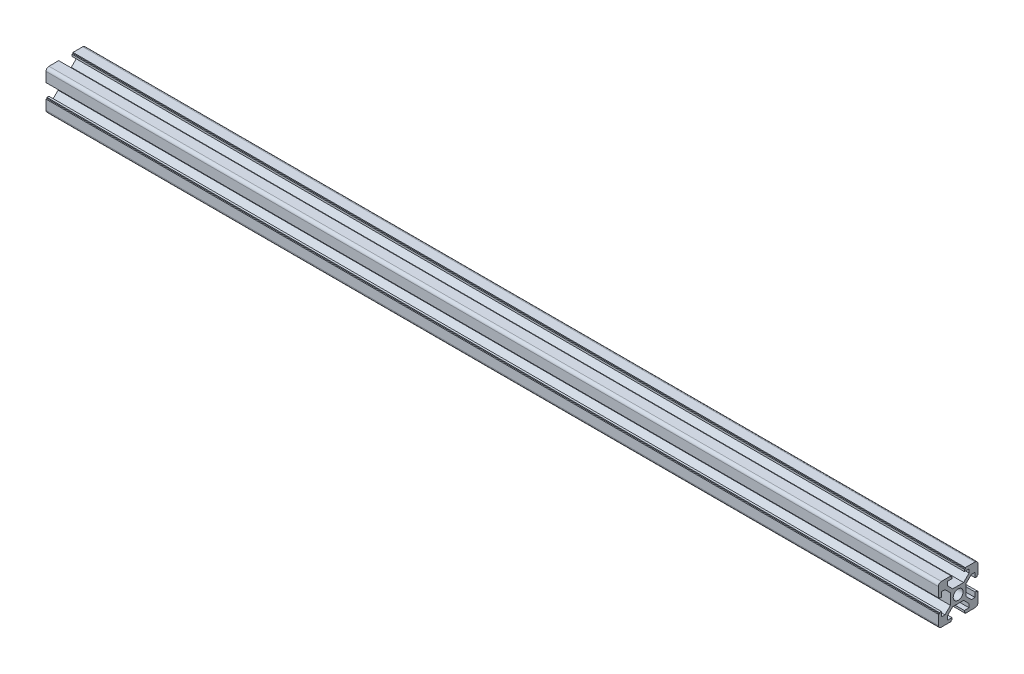
SolidWorks part; units mm, degrees
ref_plane "前视基准面" through (0, 0, 0) normal (0, 0, 1) x (1, 0, 0)
ref_plane "上视基准面" through (0, 0, 0) normal (0, 1, 0) x (1, 0, 0)
ref_plane "右视基准面" through (0, 0, 0) normal (1, 0, 0) x (0, 0, -1)
other "Configuration Table"
sketch "草图1" plane through (0, 0, 0) normal (0, 1, 0) x (1, 0, 0)
  line L0 (0, 0) -> (450, 0)
  dimension "D1" = 450
other "铝型材 20 X 20 X R1.5(1)"
ref_plane "基准面1" through (0, 0, 0) normal (1, 0, 0) x (0, 0, -1)
sketch "Sketch1" plane through (0, 0, 0) normal (1, 0, 0) x (0, 0, -1)
  line L0 (-3.6, 10) -> (-3.6, 9.5)
  line L1 (-3.6, 9.5) -> (-3.1, 9.5)
  line L2 (-3.1, 9.5) -> (-3.1, 8.5)
  line L3 (-3.1, 8.5) -> (-5.5, 8.5)
  line L4 (-8.5, -10) -> (-3.6, -10)
  line L5 (-10, -8.5) -> (-10, -3.6)
  line L6 (8.5, 10) -> (3.6, 10)
  line L7 (10, 8.5) -> (10, 3.6)
  line L8 (0, 14.8756) -> (0, 0) construction
  line L9 (0, 0) -> (14.1675, 0) construction
  line L10 (-5.5, 8.5) -> (-5.5, 6.65)
  line L11 (-5.5, 6.65) -> (-2.75, 3.9)
  line L12 (-2.75, 3.9) -> (2.75, 3.9)
  line L13 (5.5, 6.65) -> (2.75, 3.9)
  line L14 (5.5, 8.5) -> (5.5, 6.65)
  line L15 (3.1, 8.5) -> (5.5, 8.5)
  line L16 (3.1, 9.5) -> (3.1, 8.5)
  line L17 (3.6, 9.5) -> (3.1, 9.5)
  line L18 (3.6, 10) -> (3.6, 9.5)
  line L19 (-3.6, 10) -> (-8.5, 10)
  line L20 (10, 3.6) -> (9.5, 3.6)
  line L21 (9.5, 3.6) -> (9.5, 3.1)
  line L22 (9.5, 3.1) -> (8.5, 3.1)
  line L23 (8.5, 3.1) -> (8.5, 5.5)
  line L24 (8.5, 5.5) -> (6.65, 5.5)
  line L25 (6.65, 5.5) -> (3.9, 2.75)
  line L26 (3.9, 2.75) -> (3.9, -2.75)
  line L27 (6.65, -5.5) -> (3.9, -2.75)
  line L28 (8.5, -5.5) -> (6.65, -5.5)
  line L29 (8.5, -3.1) -> (8.5, -5.5)
  line L30 (9.5, -3.1) -> (8.5, -3.1)
  line L31 (9.5, -3.6) -> (9.5, -3.1)
  line L32 (10, -3.6) -> (9.5, -3.6)
  line L33 (3.6, -10) -> (3.6, -9.5)
  line L34 (3.6, -9.5) -> (3.1, -9.5)
  line L35 (3.1, -9.5) -> (3.1, -8.5)
  line L36 (3.1, -8.5) -> (5.5, -8.5)
  line L37 (5.5, -8.5) -> (5.5, -6.65)
  line L38 (5.5, -6.65) -> (2.75, -3.9)
  line L39 (2.75, -3.9) -> (-2.75, -3.9)
  line L40 (-5.5, -6.65) -> (-2.75, -3.9)
  line L41 (-5.5, -8.5) -> (-5.5, -6.65)
  line L42 (-3.1, -8.5) -> (-5.5, -8.5)
  line L43 (-3.1, -9.5) -> (-3.1, -8.5)
  line L44 (-3.6, -9.5) -> (-3.1, -9.5)
  line L45 (-3.6, -10) -> (-3.6, -9.5)
  line L46 (-10, -3.6) -> (-9.5, -3.6)
  line L47 (-9.5, -3.6) -> (-9.5, -3.1)
  line L48 (-9.5, -3.1) -> (-8.5, -3.1)
  line L49 (-8.5, -3.1) -> (-8.5, -5.5)
  line L50 (-8.5, -5.5) -> (-6.65, -5.5)
  line L51 (-6.65, -5.5) -> (-3.9, -2.75)
  line L52 (-3.9, -2.75) -> (-3.9, 2.75)
  line L53 (-6.65, 5.5) -> (-3.9, 2.75)
  line L54 (-8.5, 5.5) -> (-6.65, 5.5)
  line L55 (-8.5, 3.1) -> (-8.5, 5.5)
  line L56 (-9.5, 3.1) -> (-8.5, 3.1)
  line L57 (-9.5, 3.6) -> (-9.5, 3.1)
  line L58 (-10, 3.6) -> (-9.5, 3.6)
  line L59 (3.6, -10) -> (8.5, -10)
  line L60 (-10, 3.6) -> (-10, 8.5)
  line L61 (10, -3.6) -> (10, -8.5)
  circle A0 centre (0, 0) radius 2.5
  arc A1 (-10, 8.5) -> (-8.5, 10) centre (-8.5, 8.5) cw
  arc A2 (10, 8.5) -> (8.5, 10) centre (8.5, 8.5) ccw
  arc A3 (-8.5, -10) -> (-10, -8.5) centre (-8.5, -8.5) cw
  arc A4 (8.5, -10) -> (10, -8.5) centre (8.5, -8.5) ccw
  point P0 (-10, 0)
  point P1 (10, 0)
  point P2 (0, 10)
  point P3 (0, -10)
  point P4 (0, 0)
  point P5 (-10, -10)
  point P6 (10, -10)
  point P7 (10, 10)
  point P8 (-10, 10)
  point P13 (0, 0)
  point P36 (-10, 10)
  point P39 (10, 10)
  dimension "D1" = 11
  dimension "D2" = 20
  dimension "D3" = 6.2
  dimension "D4" = 7.2
  dimension "D5" = 6.1
  dimension "D6" = 5
  dimension "D7" = 1.5
  dimension "D8" = 45
  dimension "D9" = 0.5
  dimension "D10" = 1
  dimension "D11" = 5.5
